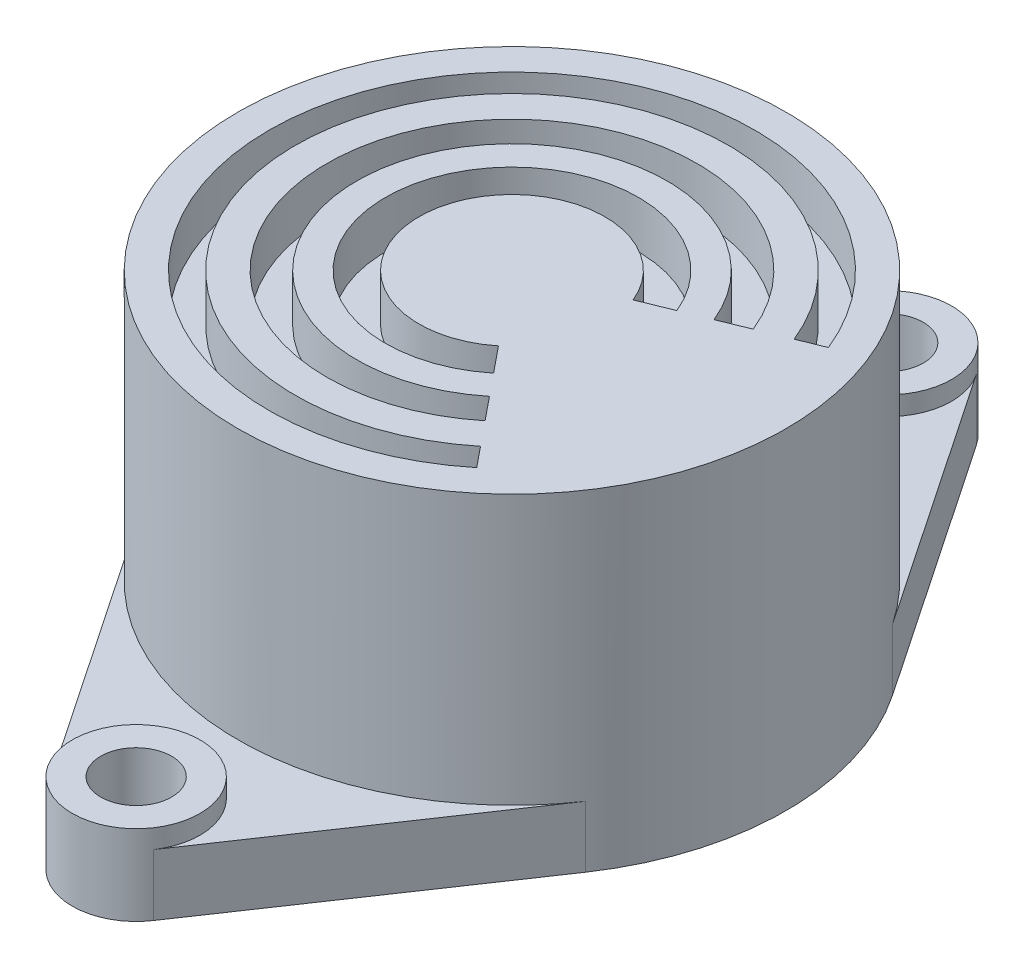
SolidWorks part; units mm, degrees
ref_plane "Front Plane" through (0, 0, 0) normal (0, 0, 1) x (1, 0, 0)
ref_plane "Top Plane" through (0, 0, 0) normal (0, 1, 0) x (1, 0, 0)
ref_plane "Right Plane" through (0, 0, 0) normal (1, 0, 0) x (0, 0, -1)
sketch "Sketch1" plane through (0, 0, 0) normal (0, 1, 0) x (1, 0, 0)
  circle A0 centre (0, 0) radius 14.732
  dimension "D1" = 29.464
extrude "Boss-Extrude1" add sketch "Sketch1" along normal blind 14.478
sketch "Sketch2" plane through (0, 0, 0) normal (0, -1, 0) x (1, 0, 0)
  line L0 (0, -20.193) -> (0, 20.193) construction
  line L2 (12.2079, 8.2462) -> (2.8415, 22.1124)
  line L3 (-2.8415, 22.1124) -> (-12.2079, 8.2462)
  line L4 (-12.2079, -8.2462) -> (-2.8415, -22.1124)
  line L6 (2.8415, -22.1124) -> (12.2079, -8.2462)
  arc A0 (-2.8415, -22.1124) -> (2.8415, -22.1124) centre (0, -20.193) ccw
  arc A1 (2.8415, 22.1124) -> (-2.8415, 22.1124) centre (0, 20.193) ccw
  circle A2 centre (0, 0) radius 14.732 construction
  arc A3 (-12.2079, 8.2462) -> (-12.2079, -8.2462) centre (0, 0) ccw
  arc A4 (12.2079, -8.2462) -> (12.2079, 8.2462) centre (0, 0) ccw
  circle A5 centre (0, -20.193) radius 1.905
  circle A6 centre (0, 20.193) radius 1.905
  dimension "D1" = 6.858
  dimension "D2" = 47.244
  dimension "D3" = 3.81
extrude "Boss-Extrude2" add sketch "Sketch2" along normal blind 3.302
sketch "Sketch3" plane through (0, 0, 0) normal (0, 1, 0) x (1, 0, 0)
  circle A0 centre (0, 20.193) radius 3.429
  circle A1 centre (0, -20.193) radius 3.429
  arc A2 (-2.8415, -22.1124) -> (2.8415, -22.1124) centre (0, -20.193) ccw construction
  circle A3 centre (0, -20.193) radius 1.905
  circle A4 centre (0, 20.193) radius 1.905
  circle A5 centre (0, -20.193) radius 1.905 construction
  circle A6 centre (0, 20.193) radius 1.905 construction
extrude "Boss-Extrude3" add sketch "Sketch3" along normal blind 1.016
sketch "Sketch4" plane through (0, 14.478, 0) normal (0, 1, 0) x (1, 0, 0)
  line L0 (4.6274, 1.8797) -> (6.2992, 2.5589)
  line L1 (3.1507, -3.8754) -> (4.289, -5.2756)
  line L2 (5.2573, -6.4666) -> (6.2772, -7.7211)
  line L3 (7.3427, -9.0316) -> (8.2338, -10.1278)
  line L4 (7.7213, 3.1366) -> (9.2192, 3.745)
  line L5 (10.784, 4.3807) -> (12.0928, 4.9124)
  arc A0 (12.0928, 4.9124) -> (8.2338, -10.1278) centre (0, 0) ccw
  arc A1 (10.784, 4.3807) -> (7.3427, -9.0316) centre (0, 0) ccw
  arc A2 (9.2192, 3.745) -> (6.2772, -7.7211) centre (0, 0) ccw
  arc A3 (7.7213, 3.1366) -> (5.2573, -6.4666) centre (0, 0) ccw
  arc A4 (6.2992, 2.5589) -> (4.289, -5.2756) centre (0, 0) ccw
  arc A5 (4.6274, 1.8797) -> (3.1507, -3.8754) centre (0, 0) ccw
extrude "Cut-Extrude1" cut sketch "Sketch4" against normal blind 2.54
